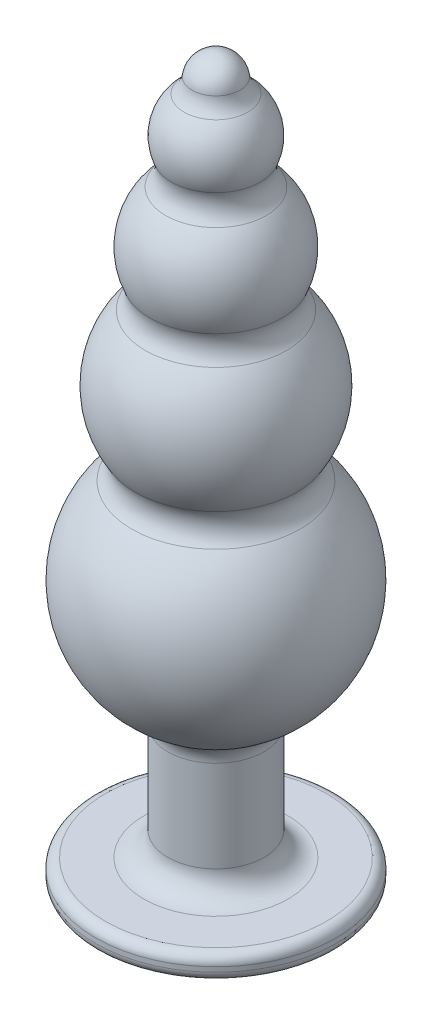
SolidWorks part; units mm, degrees
ref_plane "Front Plane" through (0, 0, 0) normal (0, 0, 1) x (1, 0, 0)
ref_plane "Top Plane" through (0, 0, 0) normal (0, 1, 0) x (1, 0, 0)
ref_plane "Right Plane" through (0, 0, 0) normal (1, 0, 0) x (0, 0, -1)
sketch "Sketch1" plane through (0, 0, 0) normal (0, 1, 0) x (1, 0, 0)
  circle A1 centre (0, 0) radius 25
extrude "Boss-Extrude1" add sketch "Sketch1" along normal blind 5
sketch "Sketch2" plane through (0, 5, 0) normal (0, 1, 0) x (1, 0, 0)
  circle A0 centre (0, 0) radius 10
extrude "Boss-Extrude2" add sketch "Sketch2" along normal blind 50
fillet "Fillet1" radius 5 1 edges at (0, 5, 10)
sketch "Sketch3" plane through (0, 55, 0) normal (0, 1, 0) x (1, 0, 0)
  line L0 (0, 25) -> (0, -25)
  arc A0 (0, 25) -> (0, -25) centre (0, 0) cw
  point P5 (0, 0)
  dimension "D1" = 50
revolve "Revolve1" add sketch "Sketch3" angle 360 about L0
fillet "Fillet2" radius 2 2 edges at (0, 0, 25) (0, 5, 25)
ref_plane "Plane1" through (0, 90, 0) normal (0, 1, 0) x (1, 0, 0)
sketch "Sketch4" plane through (0, 90, 0) normal (0, 1, 0) x (1, 0, 0)
  line L0 (0, 20) -> (0, -20)
  arc A0 (0, -20) -> (0, 20) centre (0, 0) ccw
  point P3 (0, 0)
  dimension "D1" = 40
revolve "Revolve2" add sketch "Sketch4" angle 360 about L0
ref_plane "Plane2" through (0, 115, 0) normal (0, 1, 0) x (1, 0, 0)
sketch "Sketch5" plane through (0, 115, 0) normal (0, 1, 0) x (1, 0, 0)
  line L0 (0, 15) -> (0, -15)
  arc A0 (0, -15) -> (0, 15) centre (0, 0) ccw
  point P4 (0, 0)
  dimension "D1" = 30
revolve "Revolve3" add sketch "Sketch5" angle 360 about L0
ref_plane "Plane3" through (0, 135, 0) normal (0, 1, 0) x (1, 0, 0)
sketch "Sketch6" plane through (0, 135, 0) normal (0, 1, 0) x (1, 0, 0)
  line L0 (0, 10) -> (0, -10)
  arc A0 (0, -10) -> (0, 10) centre (0, 0) ccw
  point P4 (0, 0)
  dimension "D1" = 20
revolve "Revolve4" add sketch "Sketch6" angle 360 about L0
ref_plane "Plane4" through (0, 145, 0) normal (0, 1, 0) x (1, 0, 0)
sketch "Sketch7" plane through (0, 145, 0) normal (0, 1, 0) x (1, 0, 0)
  line L0 (0, 5) -> (0, -5)
  arc A0 (0, -5) -> (0, 5) centre (0, 0) ccw
  point P4 (0, 0)
  dimension "D1" = 10
revolve "Revolve5" add sketch "Sketch7" angle 360 about L0
fillet "Fillet3" radius 5 5 edges at (0, 32.0871, 10) (-13.9971, 75.7143, 0) (-12, 106, 0) (-7.2618, 128.125, 0) (-4.8412, 143.75, 0)
